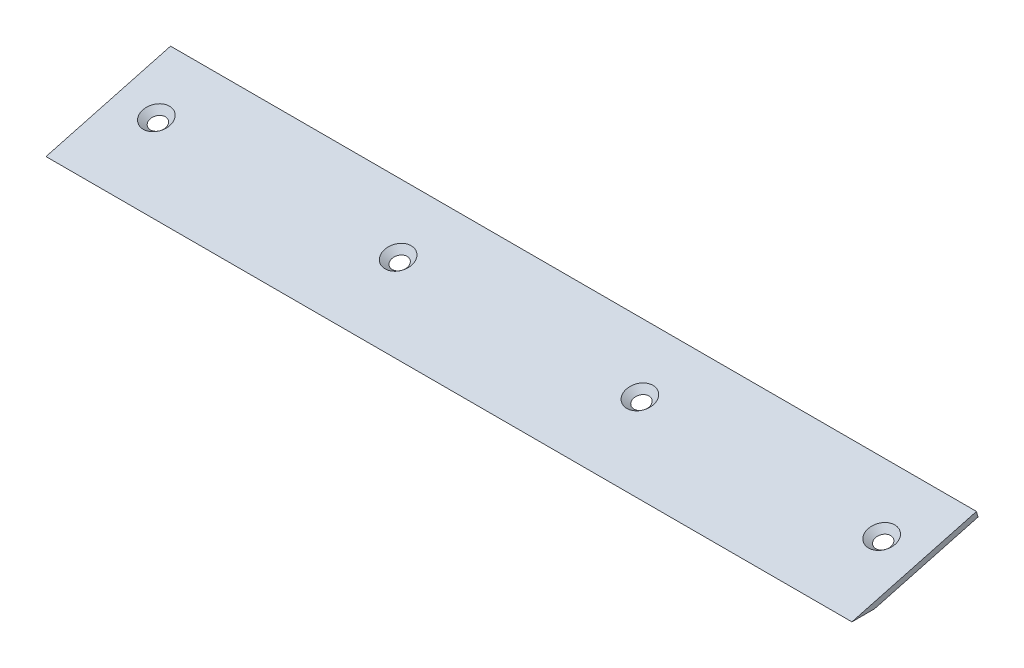
SolidWorks part; units mm, degrees
ref_plane "Alzado" through (0, 0, 0) normal (0, 0, 1) x (1, 0, 0)
ref_plane "Planta" through (0, 0, 0) normal (0, 1, 0) x (1, 0, 0)
ref_plane "Vista lateral" through (0, 0, 0) normal (1, 0, 0) x (0, 0, -1)
sketch "Croquis1" plane through (0, 0, 0) normal (1, 0, 0) x (0, 0, -1)
  line L0 (0, 0) -> (149.9636, 0) construction
  line L1 (0, 0) -> (30.9096, 8.2822)
  line L2 (30.9096, 8.2822) -> (31.2849, 6.8816)
  line L3 (31.2849, 6.8816) -> (5.6024, 0)
  line L4 (5.6024, 0) -> (0, 0)
  dimension "D1" = 15
  dimension "D2" = 1.45
  dimension "D3" = 32
extrude "Saliente-Extruir1" add sketch "Croquis1" against normal blind 200
hole_wizard "Refrentado para tornillo tapón con cabeza plana de clavija de M31" positions "Croquis7" profile "Croquis8" countersink size "M3" standard "Ansi Metric" end condition through all
sketch "Croquis7" plane through (0, 0, 0) normal (0, 0.9659, 0.2588) x (1, 0, 0)
  line L0 (-200, 32) -> (-200, 0) construction
  line L1 (-200, 32) -> (0, 32) construction
  line L2 (0, 32) -> (0, 0) construction
  point P0 (-190, 18)
  point P7 (-130, 18)
  point P9 (-70, 18)
  point P11 (-10, 18)
  dimension "D1" = 10
  dimension "D2" = 14
  dimension "D3" = 10
  dimension "D4" = 60
  dimension "D5" = 60
sketch "Croquis8" plane through (-190, 4.6587, -17.3867) normal (1, 0, 0) x (0, -0.2588, 0.9659)
  line L0 (0, 0) -> (0, 8.0971)
  line L1 (0, 8.0971) -> (1.7, 8.0971)
  line L2 (1.7, 8.0971) -> (1.7, 1.66)
  line L3 (1.7, 1.66) -> (3.36, 0)
  line L5 (3.36, 0) -> (0, 0)
  line L6 (-1.7, 1.66) -> (-3.36, 0) construction
  line L11 (0, -6.35) -> (0, 107.95) construction
  dimension "Diámetro de taladro hasta el siguiente" = 3.4
  dimension "Profundidad de taladro hasta el siguiente" = 8.0971
  dimension "Diámetro de avellanado cercano" = 6.72
  dimension "Ángulo de avellanado cercano" = 90
